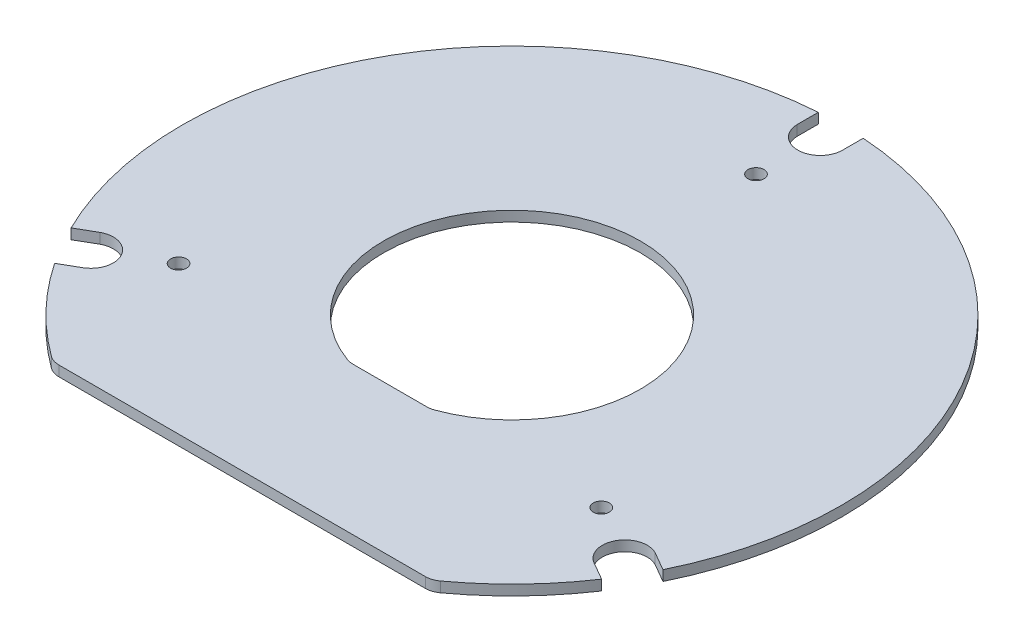
SolidWorks part; units mm, degrees
material "聚脂树脂"
ref_plane "前视基准面" through (0, 0, 0) normal (0, 0, 1) x (1, 0, 0)
ref_plane "上视基准面" through (0, 0, 0) normal (0, 1, 0) x (1, 0, 0)
ref_plane "右视基准面" through (0, 0, 0) normal (1, 0, 0) x (0, 0, -1)
other "Configuration Table"
sketch "草图1" plane through (0, 8.4, 0) normal (0, 1, 0) x (1, 0, 0)
  line L0 (-29.4767, -42) -> (29.4767, -42)
  line L3 (0, 0) -> (0, 12.182) construction
  line L5 (-3.4977, 47.8724) -> (-3.4977, 51.1922)
  line L6 (3.4977, 47.8724) -> (3.4977, 51.1922)
  line L7 (39.7099, -26.9653) -> (42.5849, -28.6252)
  line L8 (43.2075, -20.9071) -> (46.0826, -22.567)
  line L9 (-43.2075, -20.9071) -> (-46.0826, -22.567)
  line L10 (-39.7099, -26.9653) -> (-42.5849, -28.6252)
  line L11 (-6.245, -19) -> (6.245, -19)
  arc A0 (43.2075, -20.9071) -> (3.4977, 47.8724) centre (0, 0) ccw construction
  arc A1 (-3.4977, 47.8724) -> (3.4977, 47.8724) centre (0, 48) ccw
  circle A3 centre (0, 48) radius 3 construction
  arc A4 (43.2075, -20.9071) -> (39.7099, -26.9653) centre (41.5692, -24) ccw
  arc A5 (-39.7099, -26.9653) -> (-43.2075, -20.9071) centre (-41.5692, -24) ccw
  arc A6 (-39.7099, -26.9653) -> (-32.9447, -34.9091) centre (0, 0) ccw construction
  arc A7 (-3.4977, 47.8724) -> (-43.2075, -20.9071) centre (0, 0) ccw construction
  arc A8 (6.245, -19) -> (-6.245, -19) centre (0, 0) ccw
  arc A9 (32.9447, -34.9091) -> (39.7099, -26.9653) centre (0, 0) ccw construction
  circle A13 centre (0, 38) radius 1.25
  circle A14 centre (32.909, -19) radius 1.25
  circle A15 centre (-32.909, -19) radius 1.25
  arc A16 (29.4767, -42) -> (-29.4767, -42) centre (0, 0) ccw
  point P18 (0, 0)
  point P30 (-0.5211, 1.9853)
  point P47 (0, 0)
  circle M41 centre (32.909, -19) radius 0.75
  circle M42 centre (32.909, -19) radius 3
  dimension "D1" = 0.5
  dimension "D3" = 3
  dimension "D4" = 23
  dimension "D5" = 20
  dimension "D7" = 2.5
  dimension "D6" = 2.5
  dimension "D8" = 2.5
  dimension "D2" = 3
extrude "凸台-拉伸1" add sketch "草图1" along normal blind 1.6 contours L0 A16 L7 A4 L8 L6 A1 L5 L9 A5 L10 A8 L11 A13 A15 M42 | M42 M41
fillet "圆角1" radius 3 4 edges at (29.4767, 9.2, 42) (-29.4767, 9.2, 42) (-6.245, 9.2, 19) (6.245, 9.2, 19)
